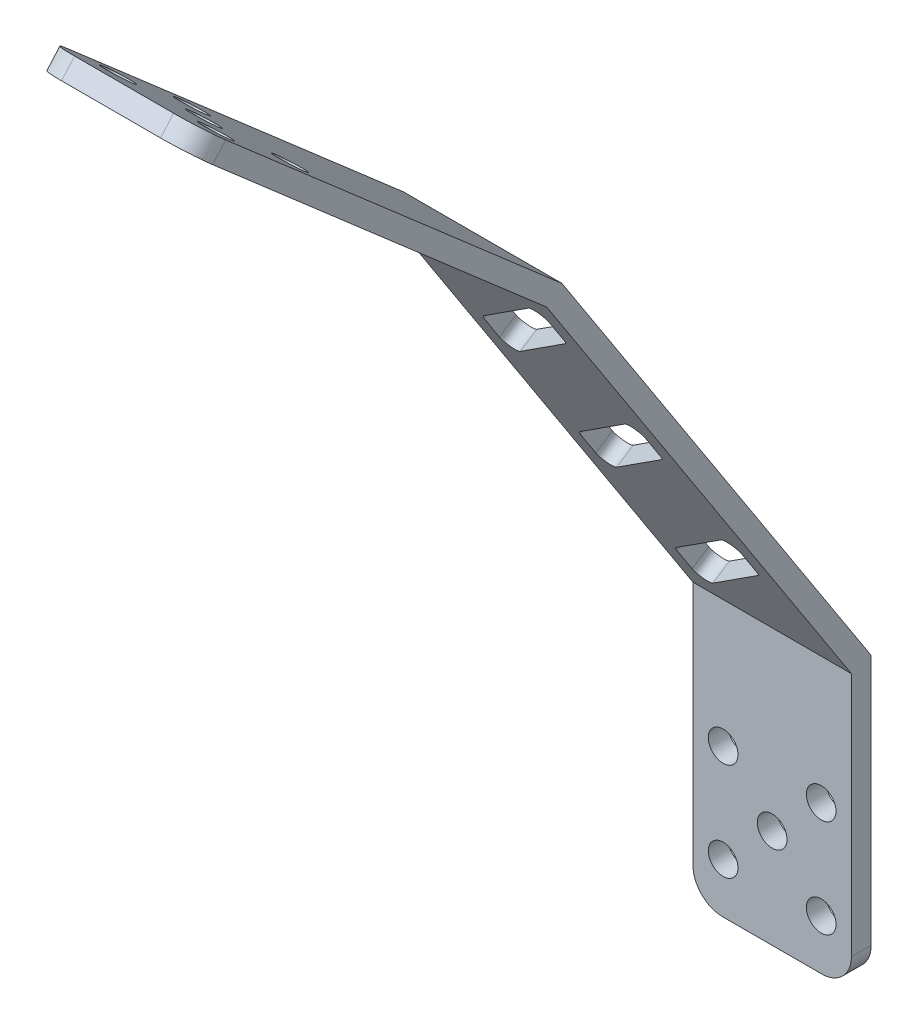
SolidWorks part; units mm, degrees
ref_plane "前视" through (0, 0, 0) normal (0, 0, 1) x (1, 0, 0)
ref_plane "上视" through (0, 0, 0) normal (0, 1, 0) x (1, 0, 0)
ref_plane "右视" through (0, 0, 0) normal (1, 0, 0) x (0, 0, -1)
sketch "草图1" plane through (0, 0, 0) normal (0, 0, 1) x (1, 0, 0)
  line L0 (0, 14.7362) -> (0, -14.2678) construction
  line L1 (-15.916, 0) -> (15.5486, 0) construction
  line L3 (-8, 24) -> (8, 24)
  line L4 (-8, 24) -> (-8, -24)
  line L5 (-8, -24) -> (8, -24)
  line L6 (8, 24) -> (8, -24)
  line L7 (-8, 24) -> (8, -24) construction
  line L8 (-8, -24) -> (8, 24) construction
  point P5 (0, 0)
  dimension "D1" = 16
  dimension "D2" = 48
extrude "凸台-拉伸1" add sketch "草图1" along normal blind 3
sketch "草图2" plane through (0, 0, 3) normal (0, 0, 1) x (1, 0, 0)
  line L0 (-7.7762, 0) -> (8.6691, 0) construction
  line L1 (0, 11.5397) -> (0, -11.8699) construction
  line L2 (-7.9817, -14) -> (8.6691, -14) construction
  line L3 (-8, -24) -> (8, -24) construction
  circle A0 centre (0, -14) radius 7 construction
  circle A1 centre (-4.9497, -9.0503) radius 1.5
  circle A2 centre (0, -14) radius 1.5
  circle A3 centre (4.9497, -9.0503) radius 1.5
  circle A4 centre (4.9497, -18.9497) radius 1.5
  circle A5 centre (-4.9497, -18.9497) radius 1.5
  point P21 (0, -14)
  dimension "D2" = 3
  dimension "D3" = 14
  dimension "D4" = 3
  dimension "D1" = 10
  dimension "D5" = 4
extrude "切除-拉伸1" cut sketch "草图2" against normal through all
ref_plane "基准面1" through (0, 12.1847, -10.592) normal (0, 0.7547, -0.6561) x (-1, 0, 0)
sketch "草图3" plane through (0, 12.1847, -10.592) normal (0, 0.7547, -0.6561) x (-1, 0, 0)
  line L0 (-8, 18.0095) -> (8, 18.0095) construction
  line L1 (-8, 18.0095) -> (8, 18.0095)
  line L2 (0, 34.8976) -> (0, -9.373) construction
  line L3 (-18.8539, 0) -> (18.6715, 0) construction
  line L4 (-8, 18.0095) -> (-8, 106.0095)
  line L5 (-8, 106.0095) -> (8, 106.0095)
  line L6 (8, 106.0095) -> (8, 18.0095)
  dimension "D1" = 88
extrude "凸台-拉伸2" add sketch "草图3" along normal blind 3 separate body
sketch "草图4" plane through (0, 11.8153, 13.592) normal (0, -0.6561, -0.7547) x (-1, 0, 0)
  line L0 (-8, 19.1449) -> (8, 19.1449) construction
  line L1 (-8, 19.1449) -> (-8, 16.1449) construction
  line L2 (-8, 16.1449) -> (8, 16.1449) construction
  line L3 (8, 19.1449) -> (8, 16.1449) construction
  line L4 (-8, 19.1449) -> (8, 19.1449)
  line L5 (-8, 19.1449) -> (-8, 16.1449)
  line L6 (-8, 16.1449) -> (8, 16.1449)
  line L7 (8, 19.1449) -> (8, 16.1449)
extrude "凸台-拉伸3" add sketch "草图4" along normal blind 2
sketch "草图5" plane through (0, 12.1847, -10.592) normal (0, -0.7547, 0.6561) x (1, 0, 0)
  line L0 (0, 80.4499) -> (0, -20.8419) construction
  line L1 (-25.5488, 95.34) -> (29.0902, 95.34) construction
  circle A0 centre (0, 95.34) radius 1.5
  circle A1 centre (0, 95.34) radius 7 construction
  circle A2 centre (-4.9497, 100.2897) radius 1.5
  circle A3 centre (4.9497, 100.2897) radius 1.5
  circle A4 centre (4.9497, 90.3903) radius 1.5
  circle A5 centre (-4.9497, 90.3903) radius 1.5
  point P19 (0, 95.34)
  dimension "D2" = 3
  dimension "D3" = 14
  dimension "D4" = 3
  dimension "D1" = 95.34
  dimension "D5" = 4
extrude "切除-拉伸2" cut sketch "草图5" against normal through all
fillet "圆角3" radius 3 4 edges at (-8, -24, 1.5) (8, -24, 1.5) (8, 82.8653, 68.4304) (-8, 82.8653, 68.4304)
sketch "草图6" plane through (-8, 0, 0) normal (-1, 0, 0) x (0, 0, 1)
  line L0 (33.5315, 50.5406) -> (3, 3.4725)
  line L1 (3, 24) -> (3, -21) construction
  line L3 (31.2445, 52.5276) -> (0, 4.3603)
  line L4 (-0.4776, 24.952) -> (65.1821, 82.0291) construction
  line L5 (0, 24) -> (0, -21) construction
  line L6 (3, 24) -> (67.1503, 79.765) construction
  line L7 (31.2445, 52.5276) -> (33.5315, 50.5406)
  line L8 (0, 4.3603) -> (3, 3.4725)
  dimension "D1" = 3
extrude "凸台-拉伸4" add sketch "草图6" against normal up to surface (16 mm away) up to face at (8, 27.0933, 17.2756)
ref_plane "基准面2" through (-8, 24.952, -0.4776) normal (0, 0.6561, 0.7547) x (1, 0, 0)
sketch "草图9" plane through (8, 0, 0) normal (1, 0, 0) x (0, 0, -1)
  line L0 (0, 4.3603) -> (-31.2445, 52.5276)
  line L1 (0.4776, 24.952) -> (-65.1821, 82.0291) construction
  line L2 (-3, 8.9852) -> (-25.3322, 43.4131) construction
  line L3 (0, -21) -> (0, 24) construction
  line L4 (0, 4.3603) -> (6.0528, 30.6803)
  line L5 (6.0528, 30.6803) -> (-31.2445, 52.5276)
extrude "切除-拉伸3" cut sketch "草图9" against normal through all
sketch "草图11" plane through (-8, 0, 0) normal (-1, 0, 0) x (0, 0, 1)
  line L0 (0, 4.3603) -> (3, 3.4725)
  line L1 (31.2445, 52.5276) -> (33.5315, 50.5406)
  line L2 (76.3463, 89.084) -> (32.7692, 51.203)
  line L3 (32.7692, 51.203) -> (2, 3.7684)
  line L4 (2, 3.7684) -> (2, -26.5916)
  line L5 (2, -26.5916) -> (76.3463, 89.084)
  line L6 (0, 4.3603) -> (0, -21) construction
  line L8 (3, 3.4725) -> (33.5315, 50.5406) construction
  line L10 (33.5315, 50.5406) -> (67.1503, 79.765) construction
  line M8 (0, -21) -> (3, -21)
  line M9 (3, -21) -> (3, 3.4725)
  line M10 (3, 3.4725) -> (33.5315, 50.5406)
  line M11 (33.5315, 50.5406) -> (67.1503, 79.765)
  line M12 (67.1503, 79.765) -> (65.1821, 82.0291)
  dimension "D1" = 2
extrude "切除-拉伸4" cut sketch "草图11" against normal through all contours L4 L5 L2 M12 M11 M10 M9 M8 | L2 L1 M12 M11 | L1 L3 L0 M10 | L0 L4 M8 M9
sketch "草图12" plane through (0, 1.2913, -1.9907) normal (0, 0.5442, -0.839) x (-1, 0, 0)
  line L0 (8, 61.0716) -> (8, 3.6581) construction
  line L1 (-6, 59.0716) -> (6, 59.0716)
  line L2 (-6, 59.0716) -> (-6, 5.6581) construction
  line L3 (-6, 5.6581) -> (6, 5.6581)
  line L4 (6, 59.0716) -> (6, 5.6581) construction
  line L5 (-8, 3.6581) -> (-8, 61.0716) construction
  line L6 (8, 61.0716) -> (-8, 61.0716) construction
  line L7 (8, 3.6581) -> (-8, 3.6581) construction
  line L8 (-6, 53.4147) -> (6, 41.4147)
  line L9 (6, 41.4147) -> (6, 47.0716)
  line L10 (6, 47.0716) -> (-6, 59.0716)
  line L11 (-6, 59.0716) -> (-6, 53.4147)
  line L12 (-6, 17.6581) -> (6, 5.6581)
  line L13 (6, 5.6581) -> (6, 11.3149)
  line L14 (6, 11.3149) -> (-6, 23.3149)
  line L15 (-6, 23.3149) -> (-6, 17.6581)
  line L16 (-6, 35.5364) -> (6, 23.5364)
  line L17 (6, 23.5364) -> (6, 29.1933)
  line L18 (6, 29.1933) -> (-6, 41.1933)
  line L19 (-6, 41.1933) -> (-6, 35.5364)
  line L20 (-6, 32.3648) -> (6, 32.3648)
  line L21 (-6, 35.5364) -> (-6, 32.3648)
  line L22 (6, 29.1933) -> (6, 32.3648)
  dimension "D1" = 2
  dimension "D2" = 2
  dimension "D3" = 2
  dimension "D4" = 2
  dimension "D5" = 4
  dimension "D6" = 45
  dimension "D7" = 4
  dimension "D8" = 4
extrude "切除-拉伸5" cut sketch "草图12" against normal through all contours L14 L15 L12 L13 | L20 L16 L17 L18 | L10 L11 L8 L9
fillet "圆角4" radius 1 12 edges at (6, 20.3073, 11.5362) (6, 15.5615, 8.4578) (-6, 5.494, 1.9274) (-6, 10.2399, 5.0058) (6, 30.5606, 18.1872) (-6, 20.4931, 11.6568) (-6, 25.2389, 14.7352) (6, 35.3064, 21.2657) (-6, 35.4922, 21.3862) (6, 45.5597, 27.9166) (-6, 40.238, 24.4646) (6, 50.3055, 30.9951)
